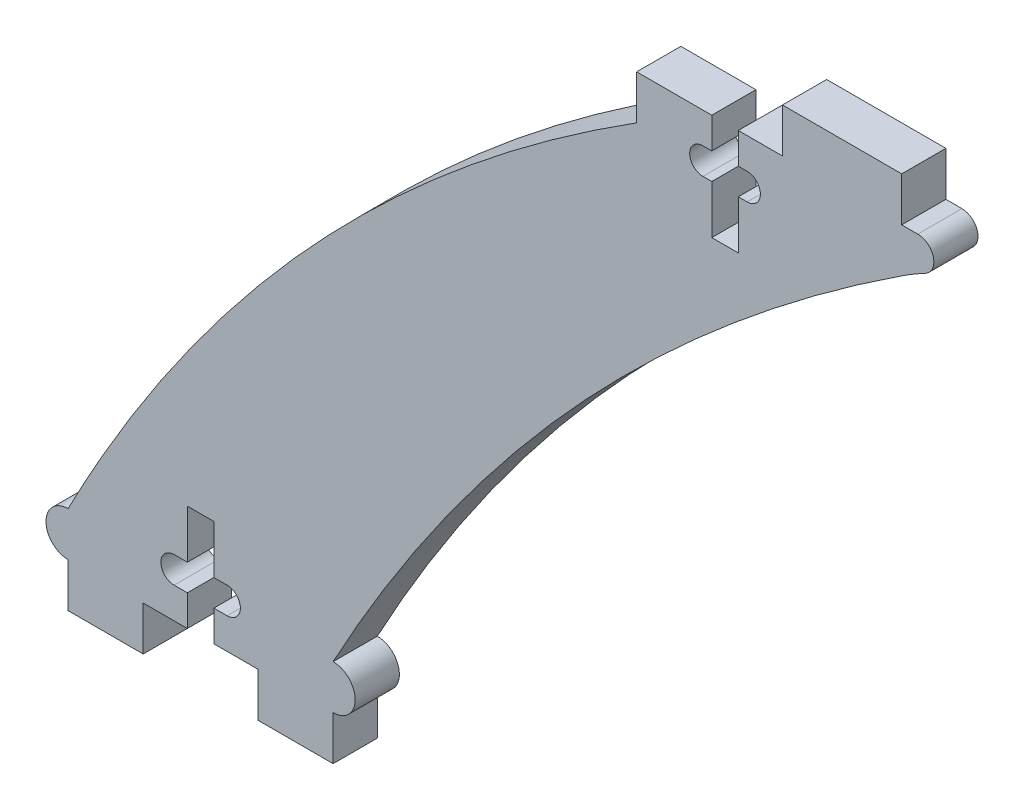
SolidWorks part; units mm, degrees
ref_plane "Front Plane" through (0, 0, 0) normal (0, 0, 1) x (1, 0, 0)
ref_plane "Top Plane" through (0, 0, 0) normal (0, 1, 0) x (1, 0, 0)
ref_plane "Right Plane" through (0, 0, 0) normal (1, 0, 0) x (0, 0, -1)
sketch "Sketch1" plane through (0, 0, 0) normal (0, 0, 1) x (1, 0, 0)
  line L1 (30, 5) -> (0, 5)
  line L2 (30, 5) -> (30, 0)
  line L3 (30, 0) -> (0, 0)
  line L4 (0, 5) -> (0, 0)
  line L5 (94.3604, 75) -> (64.3604, 75)
  line L6 (94.3604, 75) -> (94.3604, 80)
  line L7 (94.3604, 80) -> (64.3604, 80)
  line L8 (64.3604, 75) -> (64.3604, 80)
  spline S0 degree 2 poles (64.3604, 75) (22.6584, 48.7071) (0, 5) knots 0 0 0 1 1 1
  spline S1 degree 2 poles (94.3604, 75) (53.1955, 48.0273) (30, 5) knots 0 0 0 1 1 1
  dimension "D1" = 5
  dimension "D2" = 30
  dimension "D3" = 30
  dimension "D4" = 5
  dimension "D5" = 70
extrude "Boss-Extrude1" add sketch "Sketch1" along normal blind 5 contours L1 L4 L3 L2 | S1 L5 S0 L1 | L8 L5 L6 L7
sketch "Sketch3" plane through (0, 0, 5) normal (0, 0, 1) x (1, 0, 0)
  line L0 (94.3604, 80) -> (64.3604, 80) construction
  line L1 (72.8604, 80) -> (75.8604, 80)
  line L2 (72.8604, 80) -> (72.8604, 68)
  line L3 (72.8604, 68) -> (75.8604, 68)
  line L4 (75.8604, 80) -> (75.8604, 68)
  line L5 (71.8604, 75) -> (76.8604, 75) construction
  line L6 (71.8604, 76.5) -> (76.8604, 76.5)
  line L7 (71.8604, 73.5) -> (76.8604, 73.5)
  line L8 (74.3604, 80) -> (74.3604, 68) construction
  line L9 (64.3604, 75) -> (64.3604, 80) construction
  line L10 (13.5, 12) -> (16.5, 12)
  line L11 (13.5, 0) -> (16.5, 0)
  line L12 (15, 12) -> (15, 0) construction
  line L13 (13.5, 12) -> (13.5, 0)
  line L14 (16.5, 12) -> (16.5, 0)
  line L15 (12, 5) -> (18, 5) construction
  line L16 (12, 6.5) -> (18, 6.5)
  line L17 (12, 3.5) -> (18, 3.5)
  line L18 (30, 0) -> (0, 0) construction
  arc A0 (71.8604, 76.5) -> (71.8604, 73.5) centre (71.8604, 75) ccw
  arc A1 (76.8604, 73.5) -> (76.8604, 76.5) centre (76.8604, 75) ccw
  arc A2 (12, 6.5) -> (12, 3.5) centre (12, 5) ccw
  arc A3 (18, 3.5) -> (18, 6.5) centre (18, 5) ccw
  point P8 (74.3604, 75)
  point P23 (15, 5)
  line M1 (30, 0) -> (30, 5)
  spline M2 degree 2 poles (30, 5) (53.1955, 48.0273) (94.3604, 75) knots 0 0 0 1 1 1
  line M3 (94.3604, 75) -> (94.3604, 80)
  line M4 (94.3604, 80) -> (64.3604, 80)
  line M5 (64.3604, 80) -> (64.3604, 75)
  spline M6 degree 2 poles (64.3604, 75) (22.6584, 48.7071) (0, 5) knots 0 0 0 1 1 1
  line M7 (0, 5) -> (0, 0)
  line M8 (0, 0) -> (30, 0)
  dimension "D1" = 3
  dimension "D2" = 12
  dimension "D3" = 3
  dimension "D4" = 8
  dimension "D5" = 5
  dimension "D6" = 10
  dimension "D7" = 3
  dimension "D8" = 12
  dimension "D9" = 5
  dimension "D10" = 3
  dimension "D11" = 6
extrude "Cut-Extrude1" cut sketch "Sketch3" against normal blind 10 flip side to cut contours A3 L17 L14 L4 L6 A1 L7 L3 L2 A0 L13 A2 L16 L10 M8 M1 M2 M3 M4 M5 M6 M7
sketch "Sketch4" plane through (0, 0, 5) normal (0, 0, 1) x (1, 0, 0)
  line L0 (75.8604, 80) -> (75.8604, 76.5) construction
  line L1 (94.3604, 80) -> (80.8604, 80)
  line L2 (94.3604, 80) -> (94.3604, 85)
  line L3 (94.3604, 85) -> (80.8604, 85)
  line L4 (80.8604, 80) -> (80.8604, 85)
  line L5 (13.5, 3.5) -> (13.5, 0) construction
  line L6 (0, 0) -> (8.5, 0)
  line L7 (0, 0) -> (0, -5)
  line L8 (0, -5) -> (8.5, -5)
  line L9 (8.5, 0) -> (8.5, -5)
  line L10 (30, 0) -> (21.5, 0)
  line L11 (30, 0) -> (30, -5)
  line L12 (30, -5) -> (21.5, -5)
  line L13 (21.5, 0) -> (21.5, -5)
  line L14 (-905.6396, 80) -> (49094.3604, 80) construction
  line L15 (94.3604, 75) -> (94.3604, 80) construction
  line L16 (94.2858, 80) -> (96.1774, 80)
  line L17 (-970, 0) -> (49030, 0) construction
  circle A0 centre (110.9435, 50) radius 30
  circle A1 centre (96.1774, 78.183) radius 1.817
  circle A2 centre (30, 2.5) radius 2.5
  circle A3 centre (0, 2.5) radius 2.5
  line M6 (0, 0) -> (13.5, 0)
  line M18 (16.5, 0) -> (30, 0)
  line M19 (30, 0) -> (30, 5)
  line M21 (94.3604, 75) -> (94.3604, 80)
  line M22 (94.3604, 80) -> (75.8604, 80)
  dimension "D5" = 60
  dimension "D1" = 5
  dimension "D2" = 5
  dimension "D3" = 5
  dimension "D4" = 5
extrude "Boss-Extrude2" add sketch "Sketch4" against normal blind 5 contours L4 L1 L2 L3 M22 | A1 | A1 L16 M21 | A1 A0 M21 | L13 L12 L11 M18 | L9 L7 L8 M6 | A2 M19 | A2 M19 | A3
